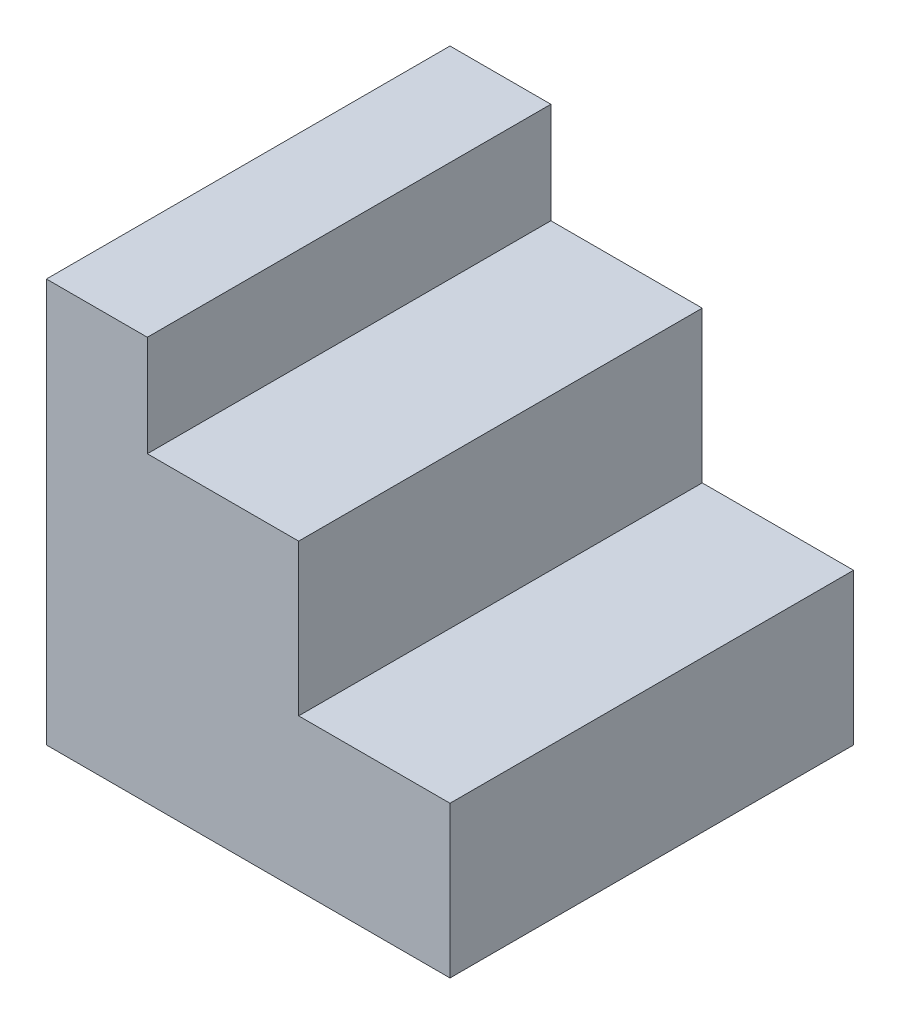
SolidWorks part; units mm, degrees
ref_plane "Front Plane" through (0, 0, 0) normal (0, 0, 1) x (1, 0, 0)
ref_plane "Top Plane" through (0, 0, 0) normal (0, 1, 0) x (1, 0, 0)
ref_plane "Right Plane" through (0, 0, 0) normal (1, 0, 0) x (0, 0, -1)
sketch "Sketch1" plane through (0, 0, 0) normal (0, 0, 1) x (1, 0, 0)
  line L1 (-20, -7.5) -> (20, -7.5)
  line L2 (-20, -7.5) -> (-20, 7.5)
  line L3 (5, 7.5) -> (20, 7.5)
  line L4 (20, -7.5) -> (20, 7.5)
  line L5 (-20, -7.5) -> (20, 7.5) construction
  line L6 (-20, 7.5) -> (20, -7.5) construction
  line L8 (-20, 7.5) -> (-20, 22.5)
  line L9 (-10, 22.5) -> (5, 22.5)
  line L10 (5, 7.5) -> (5, 22.5)
  line L12 (-20, 22.5) -> (-20, 32.5)
  line L13 (-20, 32.5) -> (-10, 32.5)
  line L14 (-10, 22.5) -> (-10, 32.5)
  point P0 (0, 0)
  dimension "D1" = 15
  dimension "D2" = 40
  dimension "D3" = 25
  dimension "D4" = 15
  dimension "D5" = 10
  dimension "D6" = 10
extrude "Boss-Extrude1" add sketch "Sketch1" along normal blind 40
